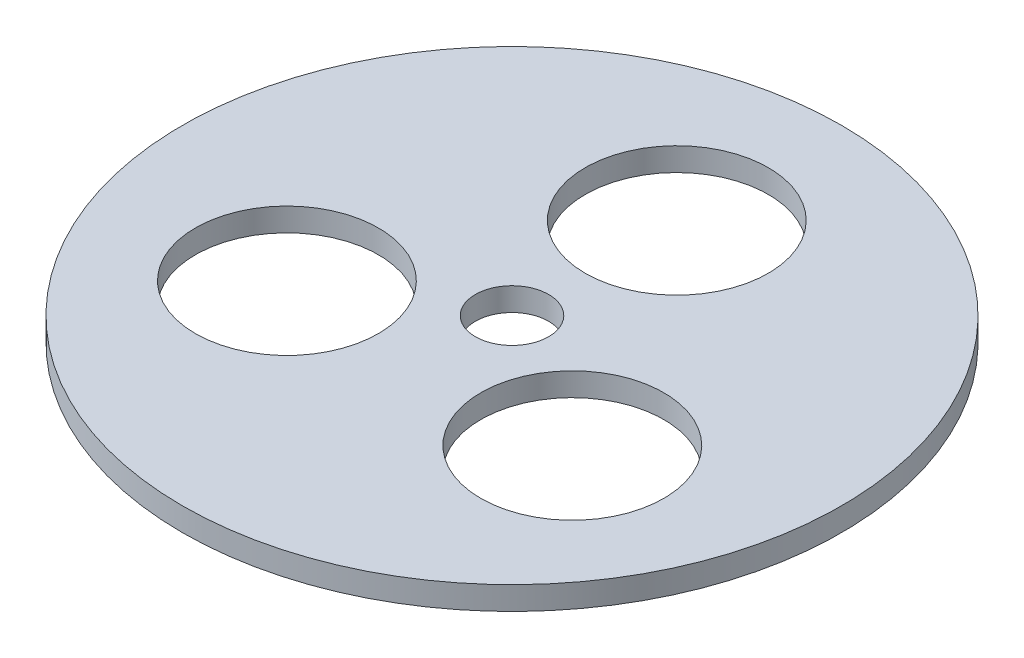
SolidWorks part; units mm, degrees
material "Acrylic (Medium-high impact)"
ref_plane "Front Plane" through (0, 0, 0) normal (0, 0, 1) x (1, 0, 0)
ref_plane "Top Plane" through (0, 0, 0) normal (0, 1, 0) x (1, 0, 0)
ref_plane "Right Plane" through (0, 0, 0) normal (1, 0, 0) x (0, 0, -1)
sketch "Sketch1" plane through (0, 0, 0) normal (0, 1, 0) x (1, 0, 0)
  line L0 (0, 0) -> (0, 45) construction
  line L1 (0, 0) -> (106.3452, -61.3984) construction
  line L2 (0, 0) -> (-119.0835, -68.7529) construction
  circle A0 centre (0, 0) radius 45
  circle A1 centre (0, 22.5) radius 12.5
  circle A2 centre (19.4856, -11.25) radius 12.5
  circle A3 centre (-19.4856, -11.25) radius 12.5
  dimension "D3" = 25
  dimension "D4" = 25
  dimension "D5" = 25
  dimension "D9" = 90
  dimension "D1" = 120
  dimension "D2" = 120
  dimension "D6" = 22.5
  dimension "D7" = 22.5
  dimension "D8" = 22.5
extrude "Boss-Extrude1" add sketch "Sketch1" along normal blind 3.175
sketch "Sketch3" plane through (0, 3.175, 0) normal (0, 1, 0) x (1, 0, 0)
  circle A0 centre (0, 0) radius 5
extrude "Cut-Extrude1" cut sketch "Sketch3" against normal blind 6.35
sketch "Sketch4" plane through (0, 0, 0) normal (0, -1, 0) x (1, 0, 0)
  line L0 (0, 5) -> (0, 60.2497) construction
  line L1 (0, 0) -> (38.9711, -22.5) construction
  line L2 (0, 0) -> (-34.1463, -19.7144) construction
  circle A0 centre (0, 0) radius 5 construction
  circle A1 centre (0, 12.5) radius 1.25
  circle A2 centre (0, 0) radius 45 construction
  circle A3 centre (10.8253, -6.25) radius 1.25
  circle A4 centre (-10.8253, -6.25) radius 1.25
  dimension "D1" = 2.5
  dimension "D2" = 120
  dimension "D3" = 120
  dimension "D4" = 12.5
extrude "Cut-Extrude2" cut sketch "Sketch4" against normal blind 1
